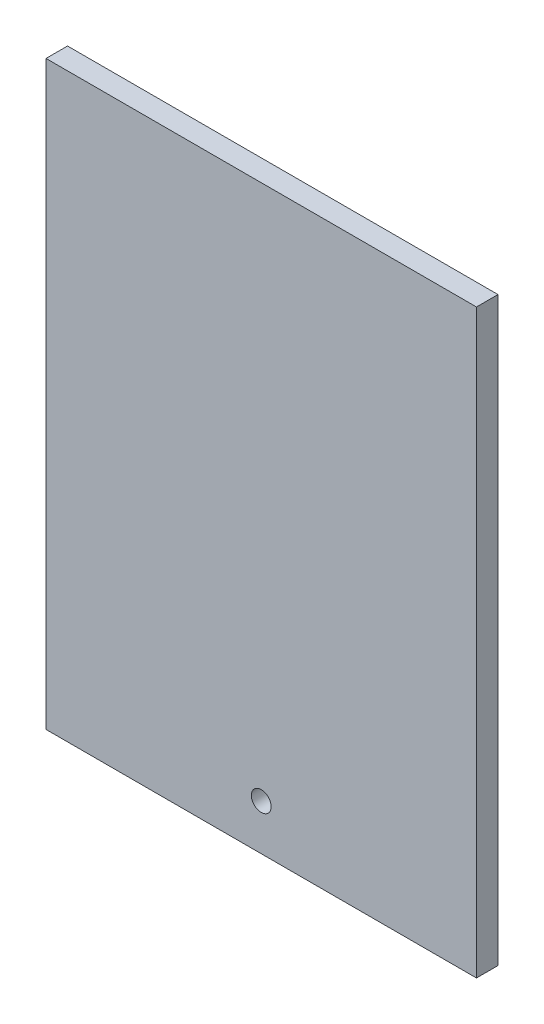
SolidWorks part; units mm, degrees
ref_plane "Front Plane" through (0, 0, 0) normal (0, 0, 1) x (1, 0, 0)
ref_plane "Top Plane" through (0, 0, 0) normal (0, 1, 0) x (1, 0, 0)
ref_plane "Right Plane" through (0, 0, 0) normal (1, 0, 0) x (0, 0, -1)
sketch "Sketch1" plane through (0, 0, 0) normal (0, 0, 1) x (1, 0, 0)
  line L1 (-63.5, 85.725) -> (63.5, 85.725)
  line L2 (-63.5, 85.725) -> (-63.5, -85.725)
  line L3 (-63.5, -85.725) -> (63.5, -85.725)
  line L4 (63.5, 85.725) -> (63.5, -85.725)
  line L5 (-63.5, 85.725) -> (63.5, -85.725) construction
  line L6 (-63.5, -85.725) -> (63.5, 85.725) construction
  point P0 (0, 0)
  dimension "D1" = 127
  dimension "D2" = 171.45
extrude "Boss-Extrude1" add sketch "Sketch1" along normal blind 6.35
sketch "Sketch2" plane through (0, 0, 6.35) normal (0, 0, 1) x (1, 0, 0)
  line L0 (0, -85.725) -> (0, -72.263) construction
  line L1 (-63.5, -85.725) -> (63.5, -85.725) construction
  circle A0 centre (0, -72.263) radius 2.921
  dimension "D2" = 5.842
  dimension "D1" = 13.462
extrude "Cut-Extrude1" cut sketch "Sketch2" against normal through all
